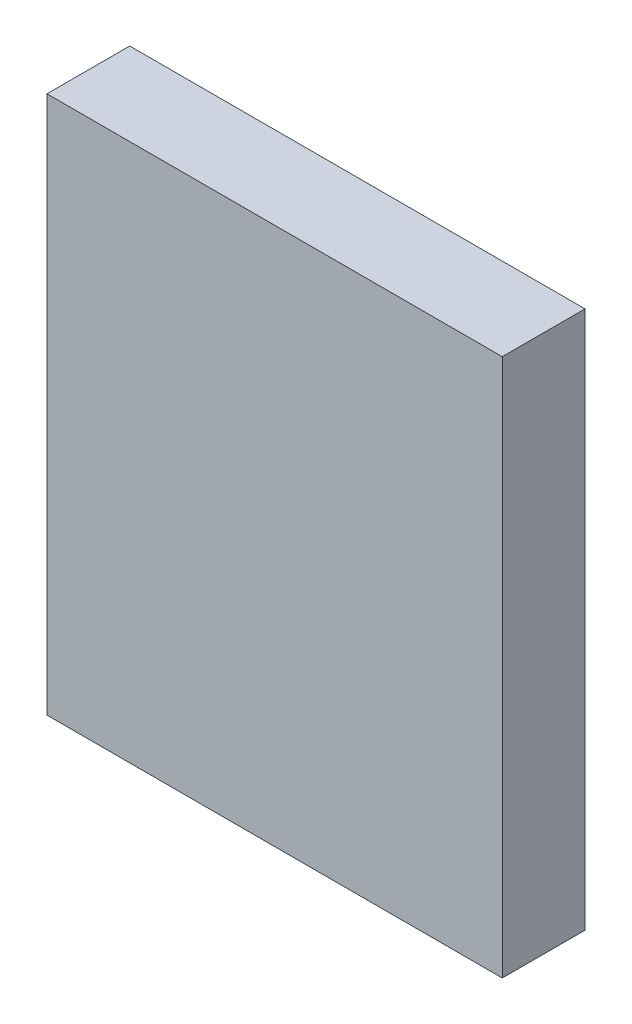
SolidWorks part; units mm, degrees
ref_plane "Plan de face" through (0, 0, 0) normal (0, 0, 1) x (1, 0, 0)
ref_plane "Plan de dessus" through (0, 0, 0) normal (0, 1, 0) x (1, 0, 0)
ref_plane "Plan de droite" through (0, 0, 0) normal (1, 0, 0) x (0, 0, -1)
sketch "Esquisse1" plane through (0, 0, 0) normal (0, 0, 1) x (1, 0, 0)
  line L1 (-34.925, 41.275) -> (34.925, 41.275)
  line L2 (-34.925, 41.275) -> (-34.925, -41.275)
  line L3 (-34.925, -41.275) -> (34.925, -41.275)
  line L4 (34.925, 41.275) -> (34.925, -41.275)
  line L5 (-34.925, 41.275) -> (34.925, -41.275) construction
  line L6 (-34.925, -41.275) -> (34.925, 41.275) construction
  point P0 (0, 0)
  dimension "D1" = 82.55
  dimension "D2" = 69.85
extrude "Boss.-Extru.1" add sketch "Esquisse1" along normal blind 12.7
